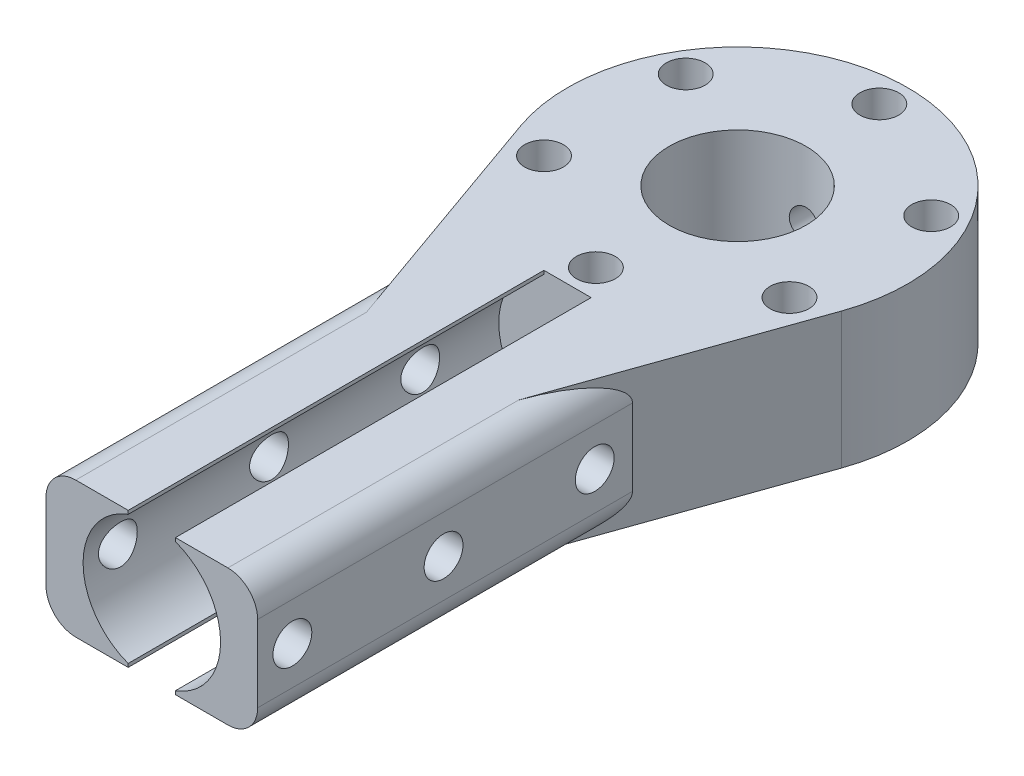
SolidWorks part; units mm, degrees
ref_plane "Front Plane" through (0, 0, 0) normal (0, 0, 1) x (1, 0, 0)
ref_plane "Top Plane" through (0, 0, 0) normal (0, 1, 0) x (1, 0, 0)
ref_plane "Right Plane" through (0, 0, 0) normal (1, 0, 0) x (0, 0, -1)
sketch "Sketch3" plane through (0, 0, 0) normal (0, 1, 0) x (1, 0, 0)
  line L0 (0, 28.575) -> (0, -73.025) construction
  line L1 (-28.3901, -9.525) -> (38.0328, -9.525) construction
  line L2 (-26.9408, -9.525) -> (-17.78, -35.4356)
  line L3 (26.9408, -9.525) -> (17.78, -35.4356)
  line L5 (-17.78, -98.425) -> (17.78, -98.425)
  line L6 (28.575, 0) -> (-28.575, 0) construction
  line L7 (-17.78, -35.4356) -> (-17.78, -98.425)
  line L8 (17.78, -35.4356) -> (17.78, -98.425)
  arc A0 (26.9408, -9.525) -> (-26.9408, -9.525) centre (0, 0) ccw
  circle A1 centre (0, 0) radius 11.5
  circle A2 centre (0, 23.8125) radius 3.2639
  circle A3 centre (20.6222, 11.9062) radius 3.2639
  circle A4 centre (20.6222, -11.9062) radius 3.2639
  circle A5 centre (0, -23.8125) radius 3.2639
  circle A6 centre (-20.6222, -11.9063) radius 3.2639
  circle A7 centre (-20.6222, 11.9063) radius 3.2639
  point P8 (0, -22.225)
  point P28 (0, 0)
  point P31 (0, 0)
  point P32 (0, 0)
  dimension "D1" = 35.56
  dimension "D2" = 38.1
  dimension "D3" = 23
  dimension "D4" = 23.8125
  dimension "D5" = 6.5278
  dimension "D6" = 6
extrude "Boss-Extrude1" add sketch "Sketch3" along normal blind 22.86
sketch "Sketch4" plane through (0, 0, 98.425) normal (0, 0, 1) x (1, 0, 0)
  line L0 (17.78, 11.43) -> (-17.78, 11.43) construction
  line L1 (17.78, 22.86) -> (17.78, 0) construction
  line L2 (-17.78, 22.86) -> (-17.78, 0) construction
  line L3 (-17.78, 22.86) -> (17.78, 22.86) construction
  line L4 (3.9687, 0) -> (-3.9688, 0)
  line L5 (3.9687, 0) -> (3.9687, 0.5833)
  line L6 (3.9687, 22.86) -> (-3.9688, 22.86)
  line L7 (-3.9688, 0) -> (-3.9688, 0.5833)
  line L8 (3.9687, 0) -> (-3.9688, 22.86) construction
  line L9 (3.9687, 22.86) -> (-3.9688, 0) construction
  line L10 (3.9687, 22.2767) -> (3.9687, 22.86)
  line L11 (-3.9688, 22.2767) -> (-3.9688, 22.86)
  arc A0 (-3.9688, 22.2767) -> (-3.9688, 0.5833) centre (0, 11.43) ccw
  arc A1 (3.9687, 0.5833) -> (3.9687, 22.2767) centre (0, 11.43) ccw
  dimension "D1" = 23.1
  dimension "D2" = 7.9375
extrude "Cut-Extrude1" cut sketch "Sketch4" against normal blind 69.85
sketch "Sketch6" plane through (17.78, 0, 0) normal (1, 0, 0) x (0, 0, -1)
  line L0 (-35.4356, 11.43) -> (-98.425, 11.43) construction
  line L1 (-35.4356, 22.86) -> (-35.4356, 0) construction
  line L2 (-98.425, 22.86) -> (-98.425, 0) construction
  line L3 (-60.8356, 11.43) -> (-123.825, 11.43) construction
  line L4 (-86.2356, 11.43) -> (-149.225, 11.43) construction
  circle A0 centre (-41.7856, 11.43) radius 3.2639
  circle A1 centre (-67.1856, 11.43) radius 3.2639
  circle A2 centre (-92.5856, 11.43) radius 3.2639
  dimension "D1" = 6.5278
  dimension "D3" = 3
  dimension "D2" = 6.35
extrude "Cut-Extrude2" cut sketch "Sketch6" against normal through all
fillet "Fillet1" radius 5 4 edges at (-17.78, 22.86, 66.9303) (-17.78, 0, 66.9303) (17.78, 0, 66.9303) (17.78, 22.86, 66.9303)
ref_plane "Plane2" through (0, 0, 10) normal (0, 0, 1) x (1, 0, 0)
sketch "Sketch8" plane through (0, 0, 10) normal (0, 0, 1) x (1, 0, 0)
  line L0 (28.575, 11.43) -> (-28.575, 11.43) construction
  line L1 (28.575, 0) -> (28.575, 22.86) construction
  line L2 (-28.575, 22.86) -> (-28.575, 0) construction
  circle A0 centre (0, 11.43) radius 2.54
extrude "Cut-Extrude4" cut sketch "Sketch8" against normal up to surface (38.4619 mm away)
